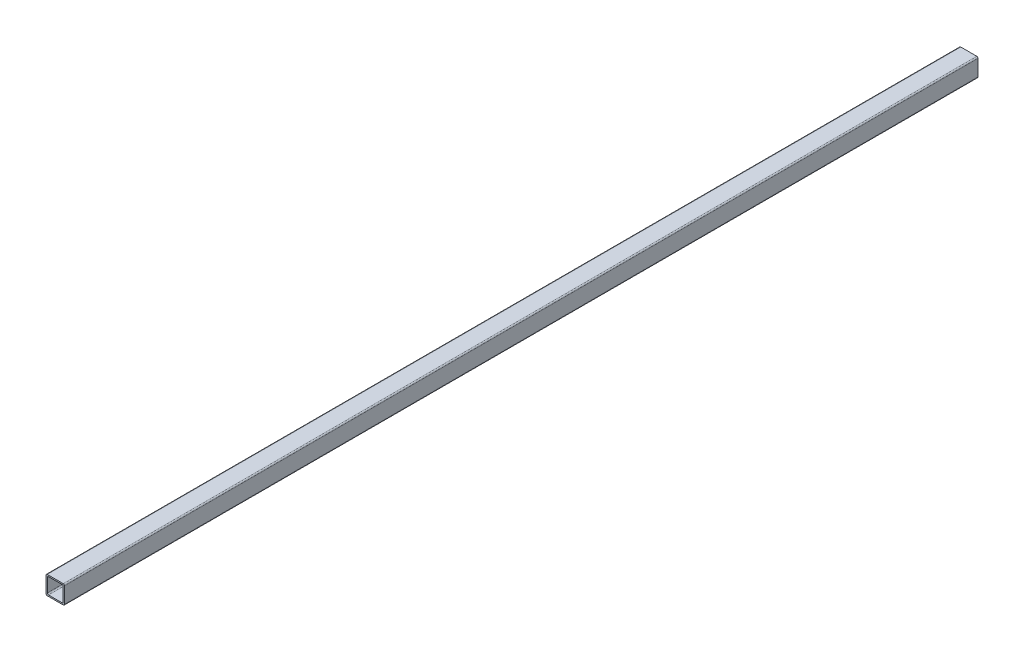
SolidWorks part; units mm, degrees
material "ASTM A500 Grade B"
ref_plane "Front Plane" through (0, 0, 0) normal (0, 0, 1) x (1, 0, 0)
ref_plane "Top Plane" through (0, 0, 0) normal (0, 1, 0) x (1, 0, 0)
ref_plane "Right Plane" through (0, 0, 0) normal (1, 0, 0) x (0, 0, -1)
sketch "Sketch1" plane through (0, 0, 0) normal (0, 0, 1) x (1, 0, 0)
  line L0 (5.3086, -2.7686) -> (32.7914, -2.7686)
  line L1 (2.54, 0) -> (35.56, 0)
  line L2 (0, -2.54) -> (0, -35.56)
  line L3 (2.54, -38.1) -> (35.56, -38.1)
  line L4 (38.1, -2.54) -> (38.1, -35.56)
  line L5 (35.3314, -5.3086) -> (35.3314, -32.7914)
  line L6 (5.3086, -35.3314) -> (32.7914, -35.3314)
  line L7 (2.7686, -5.3086) -> (2.7686, -32.7914)
  line L8 (0, 0) -> (0, -38.1) construction
  line L9 (0, -38.1) -> (38.1, -38.1) construction
  line L10 (38.1, 0) -> (38.1, -38.1) construction
  line L11 (2.7686, -2.7686) -> (2.7686, -35.3314) construction
  line L12 (2.7686, -35.3314) -> (35.3314, -35.3314) construction
  line L13 (35.3314, -2.7686) -> (35.3314, -35.3314) construction
  line L14 (2.7686, -2.7686) -> (35.3314, -2.7686) construction
  line L15 (0, 0) -> (38.1, 0) construction
  arc A0 (0, -35.56) -> (2.54, -38.1) centre (2.54, -35.56) ccw
  arc A1 (38.1, -35.56) -> (35.56, -38.1) centre (35.56, -35.56) cw
  arc A2 (2.7686, -32.7914) -> (5.3086, -35.3314) centre (5.3086, -32.7914) ccw
  arc A3 (32.7914, -35.3314) -> (35.3314, -32.7914) centre (32.7914, -32.7914) ccw
  arc A4 (35.3314, -5.3086) -> (32.7914, -2.7686) centre (32.7914, -5.3086) ccw
  arc A5 (38.1, -2.54) -> (35.56, 0) centre (35.56, -2.54) ccw
  arc A6 (0, -2.54) -> (2.54, 0) centre (2.54, -2.54) cw
  arc A7 (5.3086, -2.7686) -> (2.7686, -5.3086) centre (5.3086, -5.3086) ccw
  point P12 (0, -38.1)
  dimension "D4" = 2.54
  dimension "D3" = 2.7686
extrude "Boss-Extrude1" add sketch "Sketch1" along normal blind 1880
